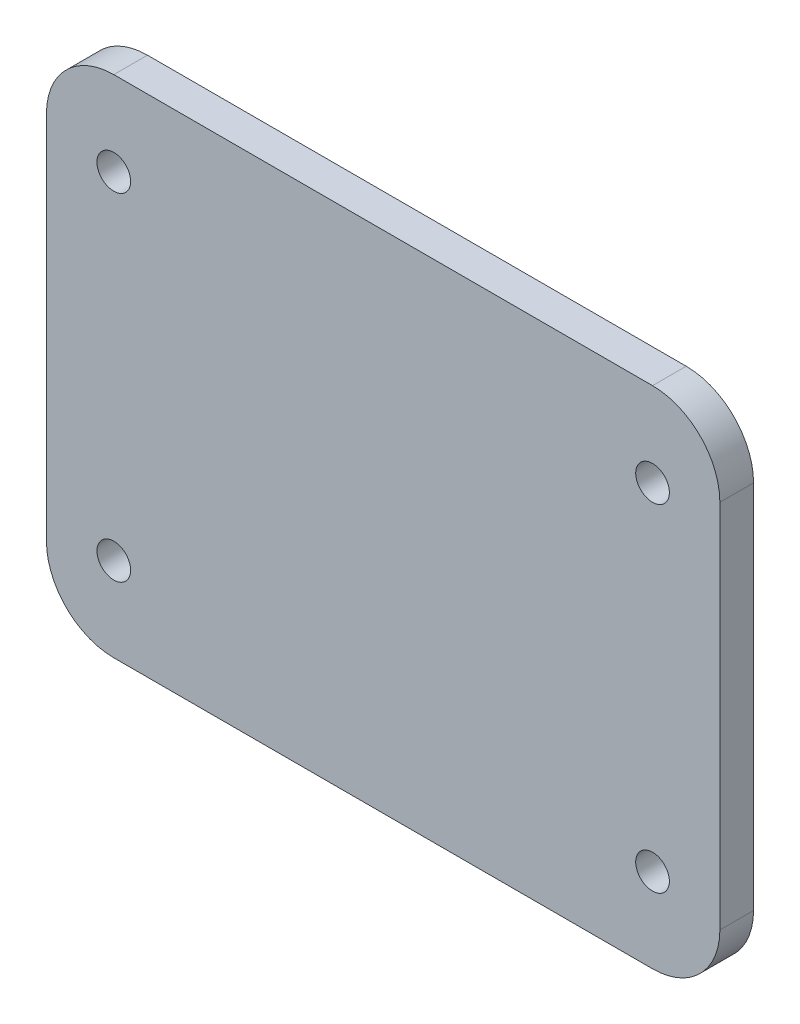
SolidWorks part; units mm, degrees
material "Plain Carbon Steel"
ref_plane "Front Plane" through (0, 0, 0) normal (0, 0, 1) x (1, 0, 0)
ref_plane "Top Plane" through (0, 0, 0) normal (0, 1, 0) x (1, 0, 0)
ref_plane "Right Plane" through (0, 0, 0) normal (1, 0, 0) x (0, 0, -1)
sketch "Sketch1" plane through (0, 0, 0) normal (0, 0, 1) x (1, 0, 0)
  line L1 (-40, -37.5) -> (40, -37.5)
  line L2 (-50, -27.5) -> (-50, 27.5)
  line L3 (-40, 37.5) -> (40, 37.5)
  line L4 (50, -27.5) -> (50, 27.5)
  line L5 (-50, -37.5) -> (50, 37.5) construction
  line L6 (-50, 37.5) -> (50, -37.5) construction
  circle A0 centre (0, 0) radius 12.5
  arc A1 (40, 37.5) -> (50, 27.5) centre (40, 27.5) cw
  arc A2 (50, -27.5) -> (40, -37.5) centre (40, -27.5) cw
  arc A3 (-40, -37.5) -> (-50, -27.5) centre (-40, -27.5) cw
  arc A4 (-40, 37.5) -> (-50, 27.5) centre (-40, 27.5) ccw
  point P0 (0, 0)
  dimension "D3" = 25
  dimension "D4" = 10
  dimension "D1" = 100
  dimension "D2" = 75
extrude "Boss-Extrude1" add sketch "Sketch1" along normal mid plane 5
sketch "Sketch2" plane through (0, 0, 2.5) normal (0, 0, 1) x (1, 0, 0)
  line L0 (50, -27.5) -> (50, 27.5) construction
  line L1 (-50, 27.5) -> (-50, -27.5) construction
  line L2 (40, 37.5) -> (-40, 37.5) construction
  circle A0 centre (40, 25) radius 2.5
  circle A1 centre (-40, 25) radius 2.5
  circle A2 centre (-40, -25) radius 2.5
  circle A3 centre (40, -25) radius 2.5
  point P0 (0, 0)
  dimension "D3" = 5
  dimension "D1" = 80
  dimension "D2" = 50
  dimension "D4" = 10
  dimension "D5" = 10
  dimension "D6" = 12.5
extrude "Cut-Extrude1" cut sketch "Sketch2" against normal through all
sketch "Sketch5" plane through (0, 0, 0) normal (0, 0, 1) x (1, 0, 0)
  circle A0 centre (0, 0) radius 12.5
  dimension "D1" = 25
extrude "Boss-Extrude2" add sketch "Sketch5" along normal mid plane 5
sketch "Sketch6" plane through (0, 0, 2.5) normal (0, 0, 1) x (1, 0, 0)
  line L0 (0, 37.5) -> (0, -37.5) construction
  line L1 (40, 37.5) -> (-40, 37.5) construction
  line L2 (-40, -37.5) -> (40, -37.5) construction
